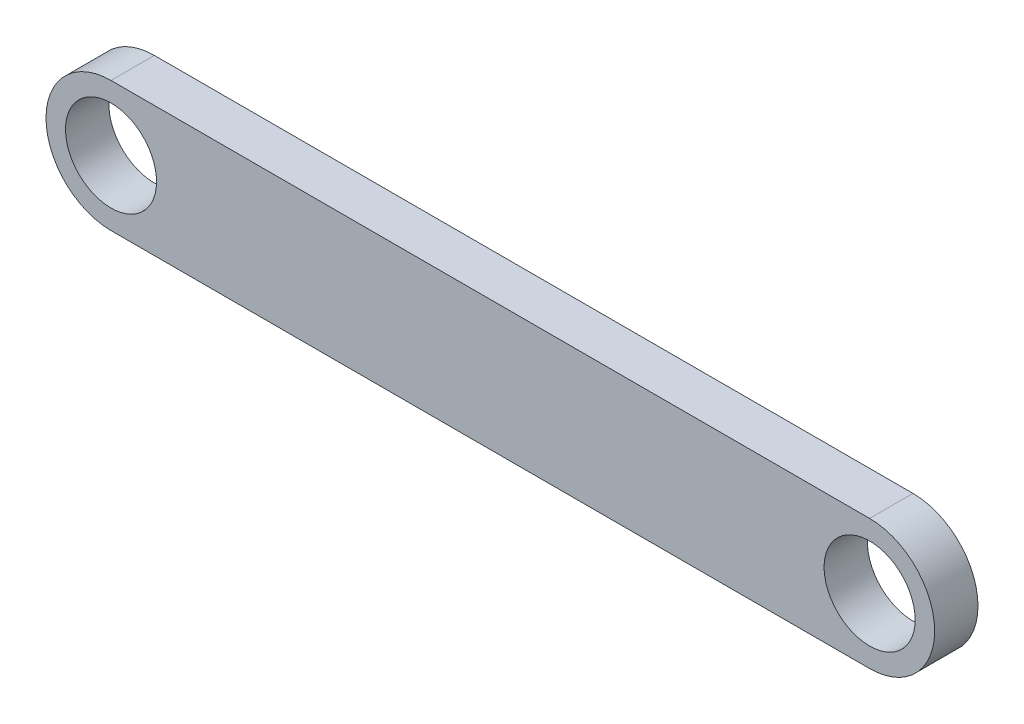
SolidWorks part; units mm, degrees
ref_plane "前视基准面" through (0, 0, 0) normal (0, 0, 1) x (1, 0, 0)
ref_plane "上视基准面" through (0, 0, 0) normal (0, 1, 0) x (1, 0, 0)
ref_plane "右视基准面" through (0, 0, 0) normal (1, 0, 0) x (0, 0, -1)
other "Configuration Table"
ref_plane "基准面1" through (0, 0, 0) normal (0, 0, -1) x (-1, 0, 0)
sketch "草图1" plane through (0, 0, 0) normal (0, 0, -1) x (-1, 0, 0)
  line L0 (20, 6) -> (-50, 6)
  line L1 (-50, -6) -> (20, -6)
  arc A0 (20, -6) -> (20, 6) centre (20, 0) ccw
  arc A1 (-50, 6) -> (-50, -6) centre (-50, 0) ccw
  circle A2 centre (20, 0) radius 4.2
  circle A3 centre (-50, 0) radius 4.2
  dimension "D1" = 8.4
  dimension "D2" = 8.4
  dimension "D3" = 70
extrude "凸台-拉伸1" add sketch "草图1" against normal blind 4
